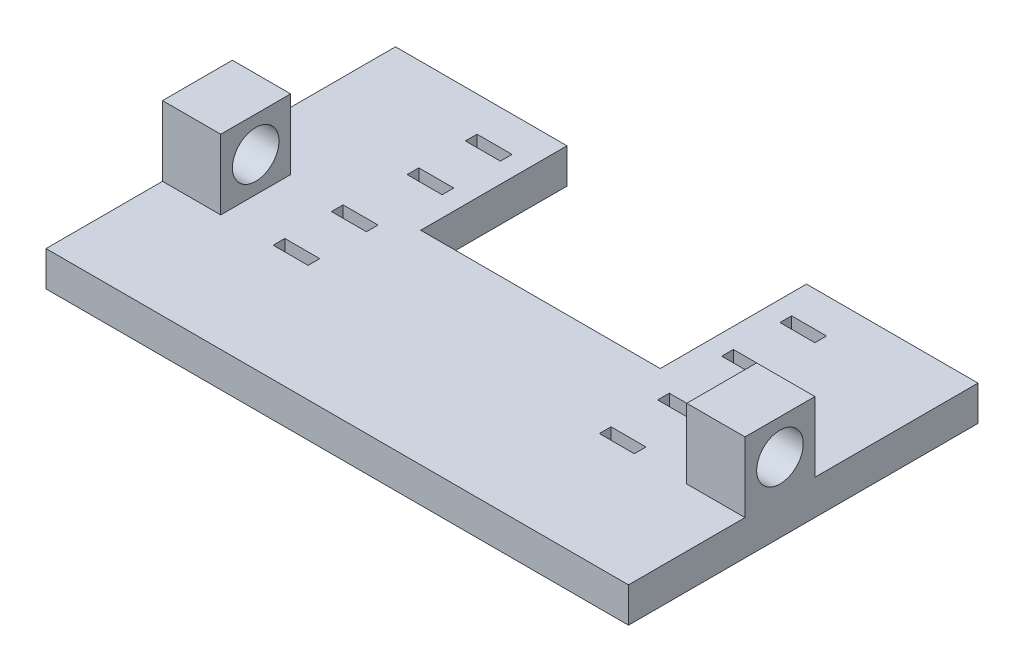
SolidWorks part; units mm, degrees
ref_plane "Front Plane" through (0, 0, 0) normal (0, 0, 1) x (1, 0, 0)
ref_plane "Top Plane" through (0, 0, 0) normal (0, 1, 0) x (1, 0, 0)
ref_plane "Right Plane" through (0, 0, 0) normal (1, 0, 0) x (0, 0, -1)
sketch "Sketch1" plane through (0, 0, 0) normal (0, 1, 0) x (1, 0, 0)
  line L0 (3, 15) -> (25, 15)
  line L1 (-25, 15) -> (-3, 15)
  line L2 (-25, 15) -> (-25, -15)
  line L3 (-25, -15) -> (25, -15)
  line L4 (25, 15) -> (25, -15)
  line L5 (-25, 15) -> (25, -15) construction
  line L6 (-25, -15) -> (25, 15) construction
  line L7 (-3, 5) -> (3, 5)
  line L8 (-3, 5) -> (-3, 13)
  line L9 (0, 10) -> (0, 0) construction
  line L10 (3, 5) -> (3, 13)
  line L11 (-3, 5) -> (3, 15) construction
  line L12 (-3, 15) -> (3, 5) construction
  line L13 (-3, 15) -> (3, 15)
  line L14 (3, 13) -> (-3, 13)
  point P0 (0, 0)
  point P6 (0, 10)
  dimension "D1" = 50
  dimension "D2" = 6
  dimension "D3" = 10
  dimension "D4" = 30
  dimension "D5" = 2
extrude "Boss-Extrude1" add sketch "Sketch1" along normal blind 3
sketch "Sketch3" plane through (0, 3, 0) normal (0, 1, 0) x (1, 0, 0)
  line L0 (-25, 15) -> (-25, -15) construction
  line L1 (-25, 1) -> (-20, 1)
  line L2 (-25, 1) -> (-25, -5)
  line L3 (-25, -5) -> (-20, -5)
  line L4 (-20, 1) -> (-20, -5)
  line L5 (25, -15) -> (25, 15) construction
  line L6 (25, 1) -> (20, 1)
  line L7 (25, 1) -> (25, -5)
  line L8 (25, -5) -> (20, -5)
  line L9 (20, 1) -> (20, -5)
  line L10 (-25, -15) -> (25, -15) construction
  dimension "D1" = 5
  dimension "D2" = 6
  dimension "D3" = 10
extrude "Boss-Extrude3" add sketch "Sketch3" along normal blind 6
sketch "Sketch4" plane through (-25, 0, 0) normal (-1, 0, 0) x (0, 0, 1)
  line L0 (-1, 3) -> (5, 9) construction
  circle A0 centre (2, 6) radius 2
  dimension "D1" = 4
extrude "Cut-Extrude1" cut sketch "Sketch4" against normal through all
sketch "Sketch5" plane through (0, 3, 0) normal (0, 1, 0) x (-1, 0, 0)
  line L1 (-3, -13) -> (3, -13)
  line L2 (-3, -13) -> (-3, -5)
  line L3 (-3, -5) -> (3, -5)
  line L4 (3, -13) -> (3, -5)
extrude "Boss-Extrude4" add sketch "Sketch5" along normal blind 6 and the other way blind 3
sketch "Sketch6" plane through (-3, 0, 0) normal (-1, 0, 0) x (0, 0, 1)
  line L0 (-13, 9) -> (-5, 3) construction
  line L1 (-5, 3) -> (-5, 9) construction
  circle A0 centre (-9, 6) radius 2
  dimension "D1" = 4
extrude "Cut-Extrude2" cut sketch "Sketch6" against normal blind 6
sketch "Sketch7" plane through (0, 3, 0) normal (0, 1, 0) x (-1, 0, 0)
  line L0 (20, 2) -> (-20, 2) construction
  line L1 (20, 4) -> (-20, 4) construction
  line L2 (20, 4) -> (20, 0) construction
  line L3 (20, 0) -> (-20, 0) construction
  line L4 (-20, 4) -> (-20, 0) construction
  line L5 (20, 5) -> (20, -1) construction
  line L6 (-20, -1) -> (-20, 5) construction
  line L7 (-20, 0) -> (20, 4) construction
  line L8 (12.5, -1) -> (-12.5, 5) construction
  line L9 (15.5, 0) -> (12.5, 0)
  line L10 (15.5, 0) -> (15.5, -1)
  line L11 (15.5, -1) -> (12.5, -1)
  line L12 (12.5, 0) -> (12.5, -1)
  line L13 (-12.5, 0) -> (-15.5, 0)
  line L14 (-12.5, 0) -> (-12.5, -1)
  line L15 (-12.5, -1) -> (-15.5, -1)
  line L16 (-15.5, 0) -> (-15.5, -1)
  line L17 (-15.5, 4) -> (-12.5, 4)
  line L18 (-15.5, 4) -> (-15.5, 5)
  line L19 (-15.5, 5) -> (-12.5, 5)
  line L20 (-12.5, 4) -> (-12.5, 5)
  line L21 (15.5, 4) -> (12.5, 4)
  line L22 (15.5, 4) -> (15.5, 5)
  line L23 (15.5, 5) -> (12.5, 5)
  line L24 (12.5, 4) -> (12.5, 5)
  point P10 (0, 2)
  point P11 (0, 2)
  point P28 (0, 2)
  dimension "D1" = 4
  dimension "D2" = 25
  dimension "D3" = 1
  dimension "D4" = 3
extrude "Cut-Extrude3" cut sketch "Sketch7" against normal blind 10
sketch "Sketch8" plane through (0, 3, 0) normal (0, 1, 0) x (1, 0, 0)
  line L0 (3, 13) -> (-3, 5) construction
  line L1 (-15, 7) -> (15, 7) construction
  line L2 (-15, 7) -> (-15, 11) construction
  line L3 (-15, 11) -> (15, 11) construction
  line L4 (15, 7) -> (15, 11) construction
  line L5 (-15, 7) -> (15, 11) construction
  line L6 (-15, 11) -> (15, 7) construction
  line L8 (-15, 11) -> (-12, 11)
  line L9 (-15, 11) -> (-15, 12)
  line L10 (-15, 12) -> (-12, 12)
  line L11 (-12, 11) -> (-12, 12)
  line L12 (15, 11) -> (12, 11)
  line L13 (15, 11) -> (15, 12)
  line L14 (15, 12) -> (12, 12)
  line L15 (12, 11) -> (12, 12)
  line L16 (-15, 7) -> (-12, 7)
  line L17 (-15, 7) -> (-15, 6)
  line L18 (-15, 6) -> (-12, 6)
  line L19 (-12, 7) -> (-12, 6)
  line L20 (15, 7) -> (12, 7)
  line L21 (15, 7) -> (15, 6)
  line L22 (15, 6) -> (12, 6)
  line L23 (12, 7) -> (12, 6)
  line L24 (-10.2793, 15.5569) -> (10.2793, 15.5569)
  line L25 (-10.2793, 15.5569) -> (-10.2793, 2.4431)
  line L26 (-10.2793, 2.4431) -> (10.2793, 2.4431)
  line L27 (10.2793, 15.5569) -> (10.2793, 2.4431)
  line L28 (-10.2793, 15.5569) -> (10.2793, 2.4431) construction
  line L29 (-10.2793, 2.4431) -> (10.2793, 15.5569) construction
  point P0 (0, 9)
  point P21 (0, 9)
  dimension "D1" = 4
  dimension "D2" = 30
  dimension "D3" = 1
  dimension "D4" = 3
extrude "Cut-Extrude4" cut sketch "Sketch8" against normal blind 10 and the other way blind 10 contours L24 L27 L26 L25
